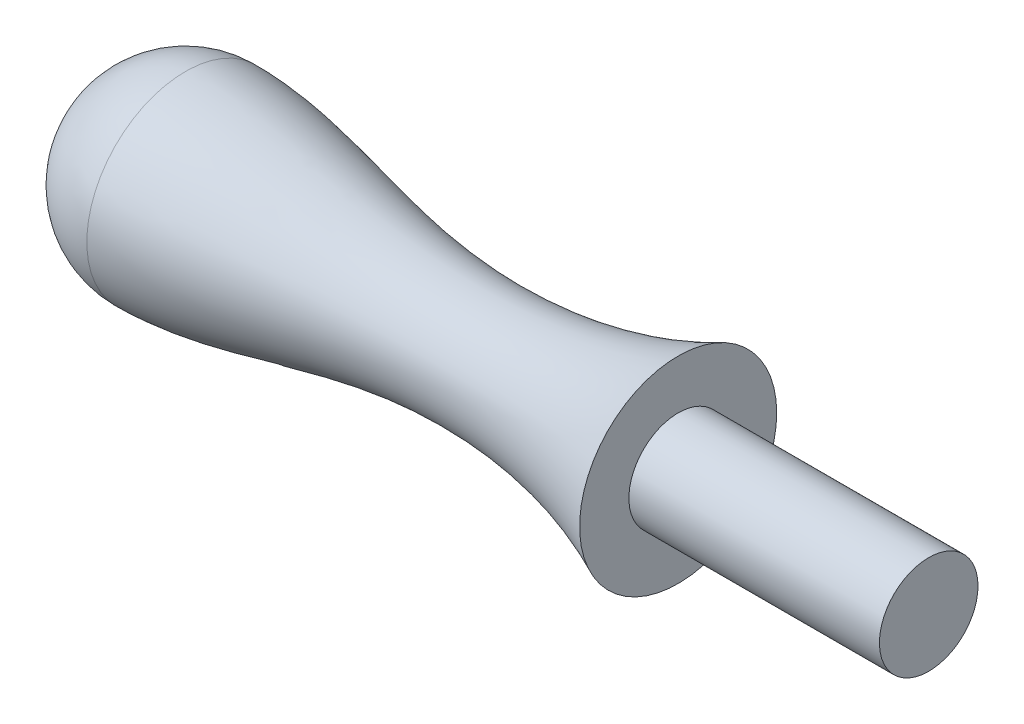
SolidWorks part; units mm, degrees
material "ABS"
ref_plane "Front Plane" through (0, 0, 0) normal (0, 0, 1) x (1, 0, 0)
ref_plane "Top Plane" through (0, 0, 0) normal (0, 1, 0) x (1, 0, 0)
ref_plane "Right Plane" through (0, 0, 0) normal (1, 0, 0) x (0, 0, -1)
sketch "Sketch1" plane through (0, 0, 0) normal (0, 1, 0) x (1, 0, 0)
  line L0 (0, 0) -> (-31.75, 0) construction
  line L1 (0, 6.35) -> (0, 0)
  line L2 (-38.1, 0) -> (-31.75, 0) construction
  line L3 (-31.75, 0) -> (0, 0)
  line L4 (-31.75, 6.35) -> (-31.75, 0) construction
  line L5 (-31.75, 6.35) -> (-36.8319, 6.35) construction
  line L6 (-38.1, 0) -> (-31.75, 0)
  arc A0 (-38.1, 0) -> (-31.75, 6.35) centre (-31.75, 0) cw
  spline S0 degree 3 poles (0, 6.35) (-5.7502, 3.6631) (-16.8937, 2.7636) (-27.1705, 6.35) (-31.75, 6.35) knots 0 0 0 0 0.57953 1 1 1 1
  dimension "D1" = 38.1
  dimension "D2" = 6.35
  dimension "D3" = 6.35
revolve "Revolve1" add sketch "Sketch1" angle 360 about L0
sketch "Sketch2" plane through (0, 0, 0) normal (1, 0, 0) x (0, 0, -1)
  circle A0 centre (0, 0) radius 3.175
  dimension "D1" = 6.35
extrude "Boss-Extrude1" add sketch "Sketch2" along normal blind 16.1436
